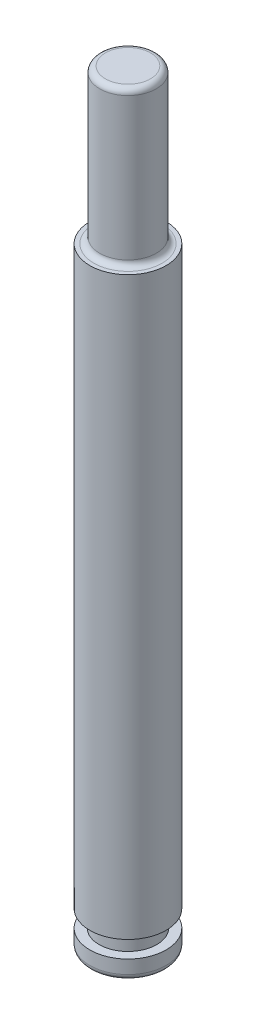
SolidWorks part; units mm, degrees
material "Stainless Steel (ferritic)"
ref_plane "Front Plane" through (0, 0, 0) normal (0, 0, 1) x (1, 0, 0)
ref_plane "Top Plane" through (0, 0, 0) normal (0, 1, 0) x (1, 0, 0)
ref_plane "Right Plane" through (0, 0, 0) normal (1, 0, 0) x (0, 0, -1)
sketch "Sketch1" plane through (0, 0, 0) normal (0, 0, 1) x (1, 0, 0)
  line L0 (0, 19.9) -> (-0.735, 19.9)
  line L1 (-0.735, 19.9) -> (-0.735, 15.9)
  line L2 (-0.735, 15.9) -> (-0.99, 15.9)
  line L3 (-0.99, 15.9) -> (-0.99, 0.94)
  line L4 (-0.99, 0.94) -> (-0.75, 0.94)
  line L5 (-0.75, 0.94) -> (-0.75, 0.5)
  line L6 (-0.75, 0.5) -> (-0.99, 0.5)
  line L7 (-0.99, 0.5) -> (-0.99, 0)
  line L8 (-0.99, 0) -> (0, 0)
  line L9 (0, 19.9) -> (0, 0) construction
  line L10 (0, 19.9) -> (0, 0)
  dimension "D1" = 19.9
  dimension "D2" = 1.98
  dimension "D3" = 4
  dimension "D4" = 1.47
  dimension "D5" = 1.5
  dimension "D6" = 0.44
  dimension "D7" = 0.5
revolve "Revolve1" add sketch "Sketch1" angle 360 about L9
fillet "Fillet1" radius 0.15 3 edges at (-0.735, 15.9, 0) (-0.99, 0, 0) (-0.735, 19.9, 0)
